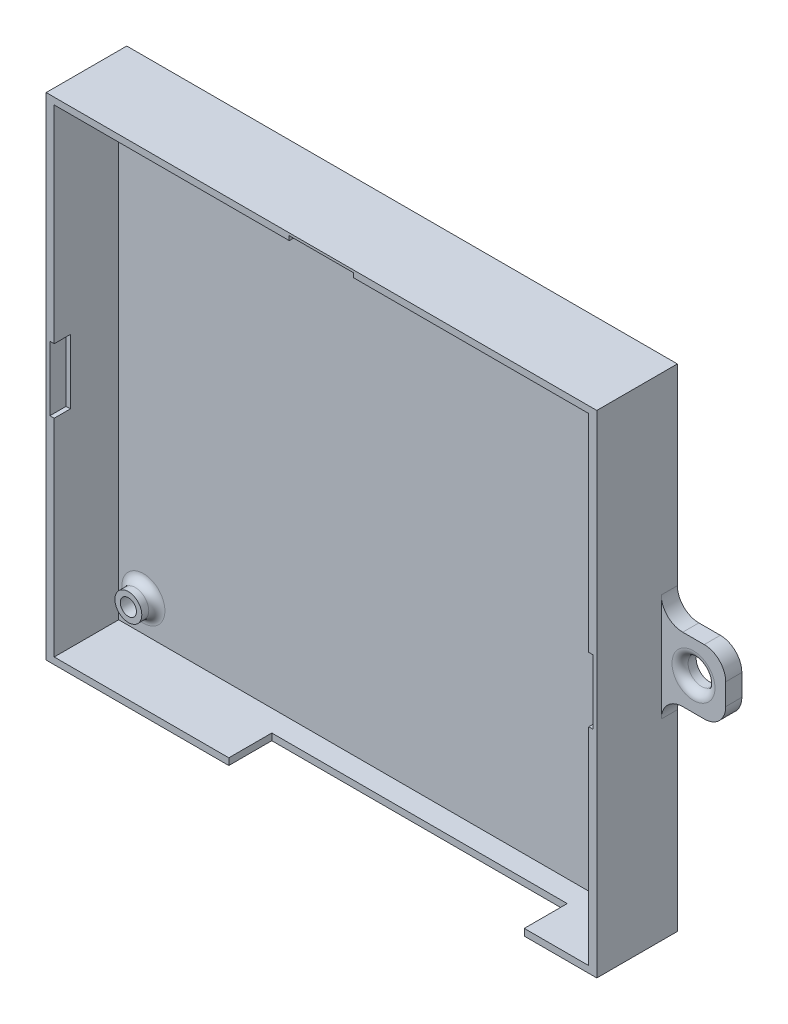
SolidWorks part; units mm, degrees
ref_plane "Спереди" through (0, 0, 0) normal (0, 0, 1) x (1, 0, 0)
ref_plane "Сверху" through (0, 0, 0) normal (0, 1, 0) x (1, 0, 0)
ref_plane "Справа" through (0, 0, 0) normal (1, 0, 0) x (0, 0, -1)
other "Configuration Table"
sketch "Эскиз1" plane through (0, 0, 0) normal (0, 0, 1) x (1, 0, 0)
  line L0 (0, 0) -> (83.9454, 0) construction
  line L1 (-51.25, 45.75) -> (51.25, 45.75)
  line L2 (-51.25, 45.75) -> (-51.25, -45.75)
  line L3 (-51.25, -45.75) -> (51.25, -45.75)
  line L4 (51.25, 45.75) -> (51.25, -45.75)
  line L5 (83.9454, 0) -> (0, 0) construction
  line L6 (0, 0) -> (-81.2162, 0) construction
  line L7 (0, 0) -> (0, 46.6803) construction
  line L8 (0, 46.6803) -> (0, -63.6094) construction
  point P6 (-51.25, 0)
  point P11 (0, 45.75)
  dimension "D1" = 102.5
  dimension "D2" = 91.5
extrude "Бобышка-Вытянуть1" add sketch "Эскиз1" along normal blind 15
sketch "Эскиз2" plane through (0, 0, 15) normal (0, 0, 1) x (1, 0, 0)
  line L1 (-49.75, 44.5) -> (49.75, 44.5)
  line L2 (-49.75, 44.5) -> (-49.75, -44.5)
  line L3 (-49.75, -44.5) -> (49.75, -44.5)
  line L4 (49.75, 44.5) -> (49.75, -44.5)
  line L6 (0, 0) -> (-59.9598, 0) construction
  line L7 (-59.9598, 0) -> (0, 0) construction
  line L8 (0, 0) -> (0, -50.6293) construction
  point P5 (-49.75, 0)
  point P9 (0, -44.5)
  dimension "D1" = 99.5
  dimension "D2" = 89
extrude "Вырез-Вытянуть1" cut sketch "Эскиз2" against normal blind 12
sketch "Эскиз3" plane through (0, 0, 15) normal (0, 0, 1) x (1, 0, 0)
  line L0 (-51.25, -45.75) -> (51.25, -45.75) construction
  line L1 (37.75, -45.75) -> (-17.25, -45.75)
  line L2 (37.75, -45.75) -> (37.75, -44.5)
  line L3 (37.75, -44.5) -> (-17.25, -44.5)
  line L4 (-17.25, -45.75) -> (-17.25, -44.5)
  line L5 (-49.75, -44.5) -> (49.75, -44.5) construction
  line L6 (49.75, -44.5) -> (49.75, 44.5) construction
  dimension "D1" = 55
  dimension "D2" = 12
extrude "Вырез-Вытянуть2" cut sketch "Эскиз3" against normal blind 8
sketch "Эскиз8" plane through (0, 0, 3) normal (0, 0, 1) x (1, 0, 0)
  line L0 (49.75, 44.5) -> (-49.75, 44.5) construction
  line L1 (49.75, -44.5) -> (49.75, 44.5) construction
  line L2 (-49.75, -44.5) -> (49.75, -44.5) construction
  line L3 (-49.75, 44.5) -> (-49.75, -44.5) construction
  circle A0 centre (-45.15, 39.5) radius 1.5
  circle A2 centre (44.75, 39.5) radius 1.5
  circle A3 centre (-45.15, -38.75) radius 1.5
  circle A5 centre (45.35, -39.9) radius 1.5
  dimension "D1" = 89.9
  dimension "D2" = 78.25
  dimension "D3" = 90.5073
  dimension "D4" = 79.4
  dimension "D5" = 5
  dimension "D6" = 4.6
  dimension "D7" = 5
  dimension "D8" = 5
  dimension "D9" = 4.4
  dimension "D10" = 4.6
  dimension "D11" = 4.6
  dimension "D12" = 5.75
extrude "Бобышка-Вытянуть2" add sketch "Эскиз8" along normal blind 0.1
sketch "Эскиз9" plane through (0, 0, 3) normal (0, 0, 1) x (1, 0, 0)
  circle A0 centre (-45.15, 39.5) radius 2.5
  circle A1 centre (44.75, 39.5) radius 2.5
  circle A2 centre (-45.15, -38.75) radius 2.5
  circle A3 centre (45.35, -39.9) radius 2.5
extrude "Бобышка-Вытянуть3" add sketch "Эскиз9" along normal blind 2.8
sketch "Эскиз10" plane through (0, 0, 15) normal (0, 0, 1) x (1, 0, 0)
  line L0 (0, 0) -> (-64.103, 0) construction
  line L1 (-64.103, 0) -> (66.2582, 0) construction
  line L2 (66.2582, 0) -> (0, 0) construction
  line L3 (0, 0) -> (0, 51.5546) construction
  line L4 (-49.75, -6) -> (-49.75, 6)
  line L5 (-6, 44.5) -> (6, 44.5)
  line L6 (-6, 44.5) -> (-6, 45.3)
  line L7 (-6, 45.3) -> (6, 45.3)
  line L8 (6, 44.5) -> (6, 45.3)
  line L9 (49.75, 44.5) -> (-49.75, 44.5) construction
  line L10 (-49.75, -6) -> (-50.55, -6)
  line L11 (-50.55, -6) -> (-50.55, 6)
  line L12 (-49.75, 6) -> (-50.55, 6)
  line L14 (-49.75, 44.5) -> (-49.75, -44.5) construction
  line L19 (-49.75, 44.5) -> (-49.75, -44.5) construction
  line L20 (50.55, -6) -> (50.55, 6)
  line L21 (50.55, -6) -> (49.75, -6)
  line L22 (49.75, -6) -> (49.75, 6)
  line L23 (50.55, 6) -> (49.75, 6)
  line L26 (49.75, -44.5) -> (49.75, 44.5) construction
  line L27 (49.75, -44.5) -> (49.75, 44.5) construction
  point P9 (-49.75, 0)
  point P16 (-50.55, 0)
  point P27 (49.75, 0)
  dimension "D1" = 12
  dimension "D2" = 0.8
  dimension "D3" = 0.8
  dimension "D4" = 12
  dimension "D5" = 0.8
  dimension "D6" = 12
extrude "Вырез-Вытянуть3" cut sketch "Эскиз10" against normal blind 3
sketch "Эскиз12" plane through (0, 0, 5.8) normal (0, 0, 1) x (1, 0, 0)
  circle A0 centre (-45.15, 39.5) radius 1.51
  circle A1 centre (44.75, 39.5) radius 1.51
  circle A2 centre (-45.15, -38.75) radius 1.51
  circle A3 centre (45.35, -39.9) radius 1.51
extrude "Вырез-Вытянуть4" cut sketch "Эскиз12" against normal blind 10
sketch "Эскиз13" plane through (0, 0, 0) normal (0, 0, -1) x (-1, 0, 0)
  line L1 (-41.8502, 38.0701) -> (-42.0618, 41.2963)
  line L2 (-42.0618, 41.2963) -> (-44.9615, 42.7262)
  line L3 (-44.9615, 42.7262) -> (-47.6498, 40.9299)
  line L4 (-47.6498, 40.9299) -> (-47.4382, 37.7037)
  line L5 (-47.4382, 37.7037) -> (-44.5385, 36.2738)
  line L6 (-44.5385, 36.2738) -> (-41.8502, 38.0701)
  line L19 (-42.2387, -40.7792) -> (-43.0329, -37.6451)
  line L20 (-43.0329, -37.6451) -> (-46.1442, -36.7659)
  line L21 (-46.1442, -36.7659) -> (-48.4613, -39.0208)
  line L22 (-48.4613, -39.0208) -> (-47.6671, -42.1549)
  line L23 (-47.6671, -42.1549) -> (-44.5558, -43.0341)
  line L24 (-44.5558, -43.0341) -> (-42.2387, -40.7792)
  line L25 (47.5558, -40.9099) -> (48.2235, -37.7465)
  line L26 (48.2235, -37.7465) -> (45.8176, -35.5865)
  line L27 (45.8176, -35.5865) -> (42.7442, -36.5901)
  line L28 (42.7442, -36.5901) -> (42.0765, -39.7535)
  line L29 (42.0765, -39.7535) -> (44.4824, -41.9135)
  line L30 (44.4824, -41.9135) -> (47.5558, -40.9099)
  line L31 (47.8884, 37.7812) -> (48.0077, 41.0122)
  line L32 (48.0077, 41.0122) -> (45.2693, 42.731)
  line L33 (45.2693, 42.731) -> (42.4116, 41.2188)
  line L34 (42.4116, 41.2188) -> (42.2923, 37.9878)
  line L35 (42.2923, 37.9878) -> (45.0307, 36.269)
  line L36 (45.0307, 36.269) -> (47.8884, 37.7812)
  circle A4 centre (-44.75, 39.5) radius 2.8 construction
  circle A5 centre (-45.35, -39.9) radius 2.8 construction
  circle A6 centre (45.15, -38.75) radius 2.8 construction
  circle A7 centre (45.15, 39.5) radius 2.8 construction
  dimension "D1" = 5.6
  dimension "D2" = 5.6
  dimension "D3" = 5.6
  dimension "D4" = 5.6
sketch "Эскиз14" plane through (0, 0, 0) normal (0, 0, -1) x (-1, 0, 0)
  line L0 (0, 0) -> (72.1199, 0) construction
  line L1 (72.1199, 0) -> (-84.6541, 0) construction
  line L2 (-51.25, -45.75) -> (-51.25, 45.75) construction
  line L3 (-51.25, 6) -> (-63.25, 6)
  line L4 (-51.25, 6) -> (-51.25, -6)
  line L5 (-51.25, -6) -> (-63.25, -6)
  line L6 (-63.25, 6) -> (-63.25, -6)
  line L7 (51.25, 45.75) -> (51.25, -45.75) construction
  line L8 (51.25, 6) -> (63.25, 6)
  line L9 (51.25, 6) -> (51.25, -6)
  line L10 (51.25, -6) -> (63.25, -6)
  line L11 (63.25, 6) -> (63.25, -6)
  point P10 (-51.25, 0)
  point P17 (51.25, 0)
  dimension "D1" = 12
  dimension "D2" = 12
  dimension "D3" = 12
  dimension "D4" = 12
extrude "Бобышка-Вытянуть4" add sketch "Эскиз14" against normal blind 3
fillet "Скругление4" radius 4 8 edges at (63.25, -6, 1.5) (63.25, 6, 1.5) (-63.25, -6, 1.5) (-63.25, 6, 1.5) (-51.25, 6, 1.5) (-51.25, -6, 1.5) (51.25, 6, 1.5) (51.25, -6, 1.5)
sketch "Эскиз15" plane through (0, 0, 3) normal (0, 0, 1) x (1, 0, 0)
  line L0 (0, 0) -> (82.5653, 0) construction
  line L1 (82.5653, 0) -> (-90.2366, 0) construction
  line L2 (-51.25, 10) -> (-51.25, -10) construction
  line L3 (51.25, -45.75) -> (51.25, 45.75) construction
  circle A0 centre (-57.25, 0) radius 2.5
  circle A1 centre (57.25, 0) radius 2.5
  dimension "D1" = 6
  dimension "D2" = 6
extrude "Вырез-Вытянуть5" cut sketch "Эскиз15" against normal blind 3
fillet "Скругление5" radius 1.5 2 edges at (-54.75, 0, 3) (59.75, 0, 3)
extrude "Вырез-Вытянуть6" cut sketch "Эскиз13" against normal blind 2
fillet "Скругление6" radius 1.5 4 edges at (-42.65, 39.5, 3) (47.25, 39.5, 3) (47.85, -39.9, 3) (-42.65, -38.75, 3)
fillet "Скругление7" radius 0.5 24 edges at (47.544, 39.3168, 0) (45.9884, 36.9887, 0) (43.1944, 37.1719, 0) (41.956, 39.6832, 0) (43.5116, 42.0113, 0) (46.3056, 41.8281, 0) (48.0642, -40.5878, 0) (47.3028, -37.8933, 0) (44.5886, -37.2055, 0) (42.6358, -39.2122, 0) (43.3972, -41.9067, 0) (46.1114, -42.5945, 0) (-47.0206, -36.6665, 0) (-44.2809, -36.0883, 0) (-42.4103, -38.1718, 0) (-43.2794, -40.8335, 0) (-46.0191, -41.4117, 0) (-47.8897, -39.3282, 0) (-42.3519, 39.6033, 0) (-43.6615, 37.1284, 0) (-46.4596, 37.0251, 0) (-47.9481, 39.3967, 0) (-46.6385, 41.8716, 0) (-43.8404, 41.9749, 0)
